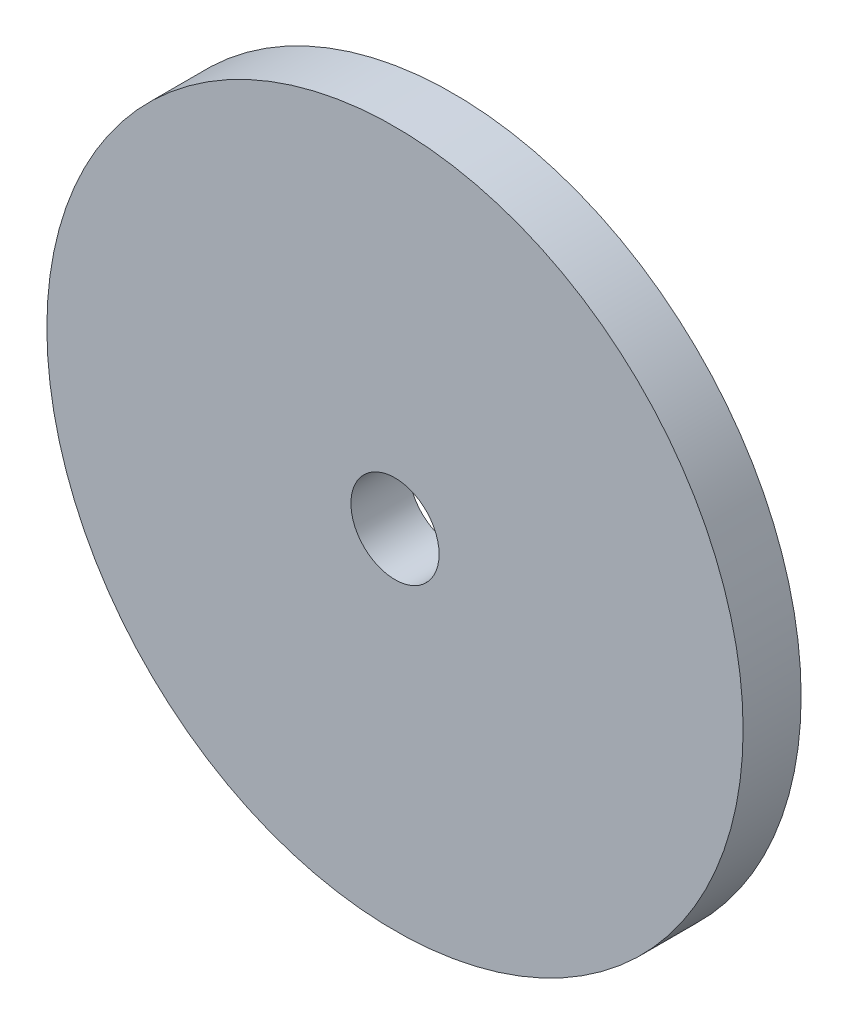
SolidWorks part; units mm, degrees
material "Oak"
ref_plane "Front Plane" through (0, 0, 0) normal (0, 0, 1) x (1, 0, 0)
ref_plane "Top Plane" through (0, 0, 0) normal (0, 1, 0) x (1, 0, 0)
ref_plane "Right Plane" through (0, 0, 0) normal (1, 0, 0) x (0, 0, -1)
sketch "Sketch1" plane through (0, 0, 0) normal (0, 0, 1) x (1, 0, 0)
  circle A0 centre (0, 0) radius 76.2
  dimension "D1" = 152.4
extrude "Boss-Extrude1" add sketch "Sketch1" along normal mid plane 12.7
hole_wizard "Ø5.0mm Dowel Hole1" positions "Sketch4" profile "Sketch3" hole size "Ø5.0" standard "ANSI Metric" end condition through all
sketch "Sketch4" plane through (0, 0, 6.35) normal (0, 0, 1) x (1, 0, 0)
  point P0 (0, 0)
sketch "Sketch3" plane through (0, 0, 6.35) normal (1, 0, 0) x (0, -1, 0)
  line L0 (0, 0) -> (0, 12.7)
  line L1 (0, 12.7) -> (9.652, 12.7)
  line L2 (9.652, 12.7) -> (9.652, 0)
  line L5 (9.652, 0) -> (0, 0)
  line L11 (0, -6.35) -> (0, 107.95) construction
  dimension "Thru Hole Dia." = 19.304
  dimension "Thru Hole Depth" = 12.7
